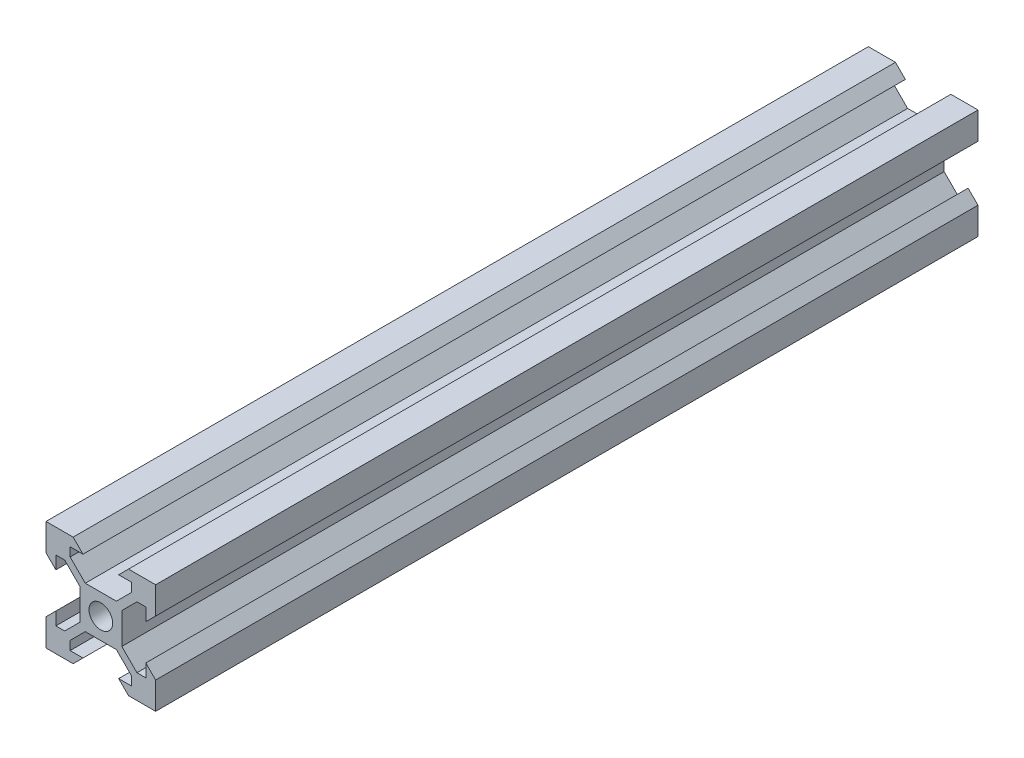
SolidWorks part; units mm, degrees
ref_plane "Alzado" through (0, 0, 0) normal (0, 0, 1) x (1, 0, 0)
ref_plane "Planta" through (0, 0, 0) normal (0, 1, 0) x (1, 0, 0)
ref_plane "Vista lateral" through (0, 0, 0) normal (1, 0, 0) x (0, 0, -1)
sketch "Croquis1" plane through (0, 0, 0) normal (0, 0, 1) x (1, 0, 0)
  line L0 (0, 0) -> (0, -20) construction
  line L2 (0, 0) -> (0, -0.5674)
  line L5 (6.175, -7.1649) -> (6.175, -12.8351)
  line L6 (7.1649, -13.825) -> (12.8351, -13.825)
  line L7 (13.825, -7.1649) -> (13.825, -12.8351)
  line L8 (7.1649, -6.175) -> (12.8351, -6.175)
  line L9 (6.175, -13.825) -> (13.825, -13.825) construction
  line L10 (13.825, -6.175) -> (13.825, -13.825) construction
  line L12 (10, -10) -> (32.1172, -10) construction
  line L13 (13.25, -18.2) -> (15.05, -20)
  line L14 (20, -20) -> (15.6, -20)
  line L15 (20, -20) -> (20, -15.6)
  line L16 (18.2, -15.6) -> (16.5899, -15.6)
  line L32 (15.6, -18.2) -> (15.6, -16.5899)
  line L33 (10, -10) -> (10, -23.2493) construction
  line L34 (4.4, -18.2) -> (4.4, -16.5899)
  line L35 (7.1649, -13.825) -> (4.4, -16.5899)
  line L36 (15.6, -18.2) -> (13.25, -18.2)
  line L38 (15.6, -20) -> (15.05, -20)
  line L40 (15.05, -20) -> (20, -20)
  line L41 (0, -20) -> (20, -20) construction
  line L42 (6.175, -12.8351) -> (3.4101, -15.6)
  line L43 (18.2, -13.25) -> (20, -15.05)
  line L44 (20, -20) -> (18.2, -20)
  line L45 (20, -20) -> (20, -15.05)
  line L48 (20, -15.05) -> (20, -20)
  line L49 (20, 0) -> (20, -20) construction
  line L50 (18.2, -15.6) -> (18.2, -13.25)
  line L51 (12.8351, -13.825) -> (15.6, -16.5899)
  line L52 (13.825, -12.8351) -> (16.5899, -15.6)
  line L53 (1.8, -15.6) -> (3.4101, -15.6)
  line L54 (1.8, -15.6) -> (1.8, -13.25)
  line L55 (1.8, -13.25) -> (0, -15.05)
  line L56 (0, 0) -> (20, 0) construction
  line L57 (0, -20) -> (0, -15.6)
  line L58 (0, -15.6) -> (0, -15.05)
  line L59 (0, -20) -> (4.4, -20)
  line L60 (0, -20) -> (4.95, -20)
  line L61 (6.75, -18.2) -> (4.95, -20)
  line L62 (4.4, -18.2) -> (6.75, -18.2)
  line L63 (1.8, -4.4) -> (3.4101, -4.4)
  line L64 (6.175, -7.1649) -> (3.4101, -4.4)
  line L65 (7.1649, -6.175) -> (4.4, -3.4101)
  line L66 (4.4, -1.8) -> (4.4, -3.4101)
  line L67 (4.4, -1.8) -> (6.75, -1.8)
  line L68 (6.75, -1.8) -> (4.95, 0)
  line L69 (0, 0) -> (4.4, 0)
  line L70 (4.4, 0) -> (4.95, 0)
  line L71 (0, 0) -> (0, -4.4)
  line L72 (0, 0) -> (0, -4.95)
  line L73 (1.8, -6.75) -> (0, -4.95)
  line L74 (1.8, -4.4) -> (1.8, -6.75)
  line L75 (15.6, -1.8) -> (15.6, -3.4101)
  line L76 (12.8351, -6.175) -> (15.6, -3.4101)
  line L77 (13.825, -7.1649) -> (16.5899, -4.4)
  line L78 (18.2, -4.4) -> (16.5899, -4.4)
  line L79 (18.2, -4.4) -> (18.2, -6.75)
  line L80 (18.2, -6.75) -> (20, -4.95)
  line L81 (20, 0) -> (20, -4.4)
  line L82 (20, -4.4) -> (20, -4.95)
  line L83 (20, 0) -> (15.6, 0)
  line L84 (20, 0) -> (15.05, 0)
  line L85 (13.25, -1.8) -> (15.05, 0)
  line L86 (15.6, -1.8) -> (13.25, -1.8)
  line L87 (6.175, -6.175) -> (13.825, -6.175) construction
  line L88 (6.175, -6.175) -> (6.175, -13.825) construction
  circle A0 centre (10, -10) radius 2.15
  point P69 (10, -10)
  dimension "D3" = 4.3
  dimension "D2" = 4
  dimension "D11" = 4.4
  dimension "D15" = 4.4
  dimension "D16" = 6.75
extrude "BoschBase" add sketch "Croquis1" along normal blind 150 contours L86 L75 L76 L8 L65 L66 L67 L68 L70 L69 L2 L71 L72 L73 L74 L63 L64 L5 L42 L53 L54 L55 L58 L57 L59 L60 L61 L62 L34 L35 L6 L51 L32 L36 L13 L38 L40 L14 L15 L45 L43 L50 L16 L52 L7 L77 L78 L79 L80 L82 L81
